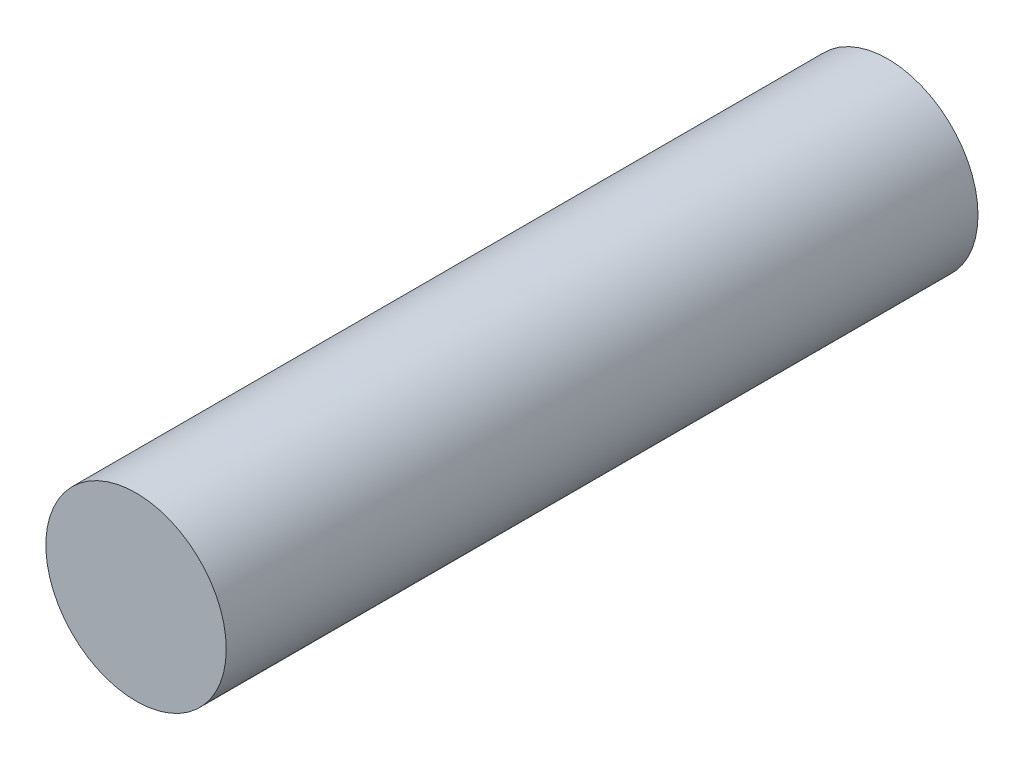
SolidWorks part; units mm, degrees
material "Stainless Steel (ferritic)"
ref_plane "Front Plane" through (0, 0, 0) normal (0, 0, 1) x (1, 0, 0)
ref_plane "Top Plane" through (0, 0, 0) normal (0, 1, 0) x (1, 0, 0)
ref_plane "Right Plane" through (0, 0, 0) normal (1, 0, 0) x (0, 0, -1)
sketch "Sketch1" plane through (0, 0, 0) normal (0, 0, 1) x (1, 0, 0)
  circle A0 centre (0, 0) radius 1.5
  dimension "D1" = 3
extrude "Boss-Extrude1" add sketch "Sketch1" along normal blind 12.5
